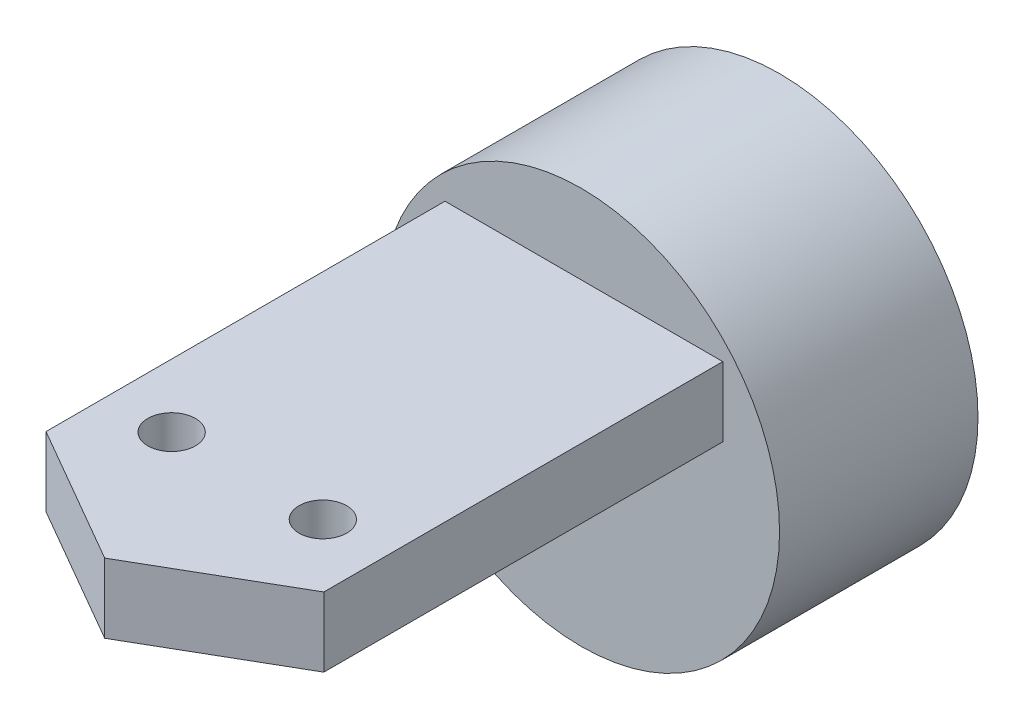
SolidWorks part; units mm, degrees
material "ABS"
ref_plane "Alzado" through (0, 0, 0) normal (0, 0, 1) x (1, 0, 0)
ref_plane "Planta" through (0, 0, 0) normal (0, 1, 0) x (1, 0, 0)
ref_plane "Vista lateral" through (0, 0, 0) normal (1, 0, 0) x (0, 0, -1)
sketch "Croquis1" plane through (0, 0, 0) normal (0, 0, 1) x (1, 0, 0)
  circle A0 centre (0, 0) radius 15
extrude "Saliente-Extruir1" add sketch "Croquis1" along normal blind 10
sketch "Croquis2" plane through (0, 0, 0) normal (0, 0, -1) x (-1, 0, 0)
  circle A0 centre (0, 0) radius 2.5
extrude "Saliente-Extruir3" add sketch "Croquis2" along normal blind 5
sketch "Croquis3" plane through (0, 0, 10) normal (0, 0, 1) x (1, 0, 0)
  line L1 (-21.5483, 2.5) -> (21.5483, 2.5)
  line L2 (-21.5483, 2.5) -> (-21.5483, -2.5)
  line L3 (-21.5483, -2.5) -> (21.5483, -2.5)
  line L4 (21.5483, 2.5) -> (21.5483, -2.5)
  line L5 (-21.5483, 2.5) -> (21.5483, -2.5) construction
  line L6 (-21.5483, -2.5) -> (21.5483, 2.5) construction
  line L7 (-13.4668, 2.5) -> (13.7477, 2.5)
  line L8 (-13.4668, 2.5) -> (-13.4668, 6)
  line L9 (-13.4668, 6) -> (13.7477, 6)
  line L10 (13.7477, 2.5) -> (13.7477, 6)
  line L11 (-13.4668, 2.5) -> (13.7477, 6) construction
  line L12 (-13.4668, 6) -> (13.7477, 2.5) construction
  circle A0 centre (0, 0) radius 15 construction
  point P0 (0, 0)
  point P6 (0.1404, 4.25)
  dimension "D1" = 5
  dimension "D2" = 3.5
  dimension "D3" = 0
extrude "Saliente-Extruir5" add sketch "Croquis3" along normal blind 30 contours L1 L10 L9 L8
fillet "Redondeo1" radius 10 1 edges at (13.7477, 4.25, 40)
fillet "Redondeo2" radius 10 1 edges at (-13.4668, 4.25, 40)
sketch "Croquis4" plane through (0, 6, 0) normal (0, 1, 0) x (1, 0, 0)
  line L1 (-13.4668, -10) -> (13.7477, -10) construction
  line L4 (3.7477, -10) -> (-3.4668, -10)
  line L13 (0.1404, -40) -> (0.1404, -10) construction
  circle A0 centre (-2.6696, -26.0647) radius 1.2
  circle A1 centre (2.9504, -26.0647) radius 1.2
  dimension "D1" = 2.4
  dimension "D2" = 2.81
extrude "Cortar-Extruir7" cut sketch "Croquis4" against normal blind 30 contours A0 | A1
sketch "Croquis7" plane through (0, 6, 0) normal (0, 1, 0) x (1, 0, 0)
  line L0 (-1.4696, -26.0647) -> (1.7504, -26.0647)
  line L1 (-6.8596, -22.0232) -> (-6.8596, -10)
  line L2 (0.1404, -34.1476) -> (7.1404, -30.1061)
  line L3 (7.1404, -30.1061) -> (7.1404, -22.0232)
  line L4 (7.1404, -22.0232) -> (0.1404, -17.9818)
  line L5 (0.1404, -17.9818) -> (-6.8596, -22.0232)
  line L6 (-6.8596, -22.0232) -> (-6.8596, -30.1061)
  line L7 (-6.8596, -30.1061) -> (0.1404, -34.1476)
  line L8 (-13.4668, -10) -> (13.7477, -10) construction
  line L9 (-6.8596, -10) -> (7.1404, -10)
  line L10 (7.1404, -10) -> (7.1404, -22.0232)
  line L11 (-6.8596, -10) -> (-13.4668, -10)
  line L12 (-13.4668, -10) -> (-13.4668, -30)
  line L13 (-13.4668, -30) -> (-3.4668, -40)
  line L14 (-3.4668, -40) -> (3.7477, -40)
  line L15 (3.7477, -40) -> (13.7477, -30)
  line L16 (13.7477, -30) -> (13.7477, -10)
  line L17 (13.7477, -10) -> (7.1404, -10)
  circle A0 centre (-2.6696, -26.0647) radius 1.2 construction
  circle A1 centre (2.9504, -26.0647) radius 1.2 construction
  circle A2 centre (0.1404, -26.0647) radius 7 construction
  line M2 (-13.4668, -10) -> (-13.4668, -30)
  line M3 (-13.4668, -30) -> (-3.4668, -40)
  line M4 (-3.4668, -40) -> (3.7477, -40)
  line M5 (3.7477, -40) -> (13.7477, -30)
  line M6 (13.7477, -30) -> (13.7477, -10)
  line M7 (13.7477, -10) -> (-13.4668, -10)
extrude "Cortar-Extruir8" cut sketch "Croquis7" against normal blind 30 contours L10 L3 L2 L7 L6 L1 M7 M2 M3 M4 M5 M6
sketch "Croquis8" plane through (0, 0, 10) normal (0, 0, 1) x (1, 0, 0)
  circle A0 centre (0, 0) radius 10
  circle A1 centre (0, 0) radius 15
extrude "Cortar-Extruir9" cut sketch "Croquis8" against normal blind 30
sketch "Croquis9" plane through (0, 6, 0) normal (0, 1, 0) x (1, 0, 0)
  circle A0 centre (-2.6696, -26.0647) radius 1.2398
  circle A1 centre (2.9504, -26.0647) radius 1.2289
extrude "Saliente-Extruir6" add sketch "Croquis9" against normal blind 3.5
sketch "Croquis10" plane through (0, 6, 0) normal (0, 1, 0) x (1, 0, 0)
  line L0 (0.1404, -34.1476) -> (0.1404, -10) construction
  line L1 (-6.8596, -10) -> (7.1404, -10) construction
  circle A0 centre (-3.6696, -26.9651) radius 1.2
  circle A1 centre (3.9504, -26.9651) radius 1.2
  dimension "D1" = 3.81
extrude "Cortar-Extruir11" cut sketch "Croquis10" against normal blind 3.5
